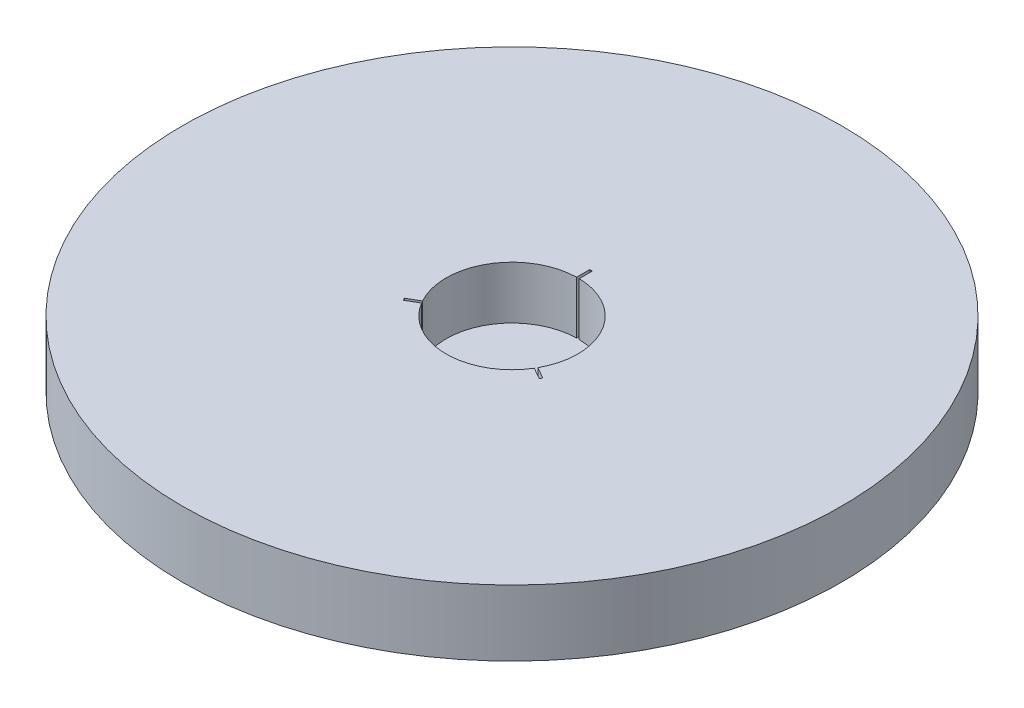
SolidWorks part; units mm, degrees
ref_plane "前基準面" through (0, 0, 0) normal (0, 0, 1) x (1, 0, 0)
ref_plane "上基準面" through (0, 0, 0) normal (0, 1, 0) x (1, 0, 0)
ref_plane "右基準面" through (0, 0, 0) normal (1, 0, 0) x (0, 0, -1)
sketch "草圖2" plane through (0, 0, 0) normal (0, 1, 0) x (1, 0, 0)
  line L0 (26.2264, -14.5645) -> (25.7264, -15.4305)
  line L1 (-0.5, 29.995) -> (0.5, 29.995)
  line L2 (-0.5, 29.995) -> (-0.5, 24.995)
  line L3 (0.5, 29.995) -> (0.5, 24.995)
  line L4 (-0.5, 29.995) -> (0.5, 24.995) construction
  line L5 (-0.5, 24.995) -> (0.5, 29.995) construction
  line L6 (26.2264, -14.5645) -> (21.8963, -12.0645)
  line L7 (25.7264, -15.4305) -> (21.3963, -12.9305)
  line L8 (26.2264, -14.5645) -> (21.3963, -12.9305) construction
  line L9 (21.8963, -12.0645) -> (25.7264, -15.4305) construction
  line L10 (-25.7264, -15.4305) -> (-26.2264, -14.5645)
  line L11 (-25.7264, -15.4305) -> (-21.3963, -12.9305)
  line L12 (-26.2264, -14.5645) -> (-21.8963, -12.0645)
  line L13 (-25.7264, -15.4305) -> (-21.8963, -12.0645) construction
  line L14 (-21.3963, -12.9305) -> (-26.2264, -14.5645) construction
  circle A0 centre (0, 0) radius 125
  arc A6 (-0.5, 24.995) -> (-21.8963, -12.0645) centre (0, 0) ccw
  arc A7 (-21.3963, -12.9305) -> (21.3963, -12.9305) centre (0, 0) ccw
  arc A8 (21.8963, -12.0645) -> (0.5, 24.995) centre (0, 0) ccw
  point P5 (0, 27.495)
  point P14 (0, 0)
  dimension "D1" = 250
  dimension "D2" = 50
  dimension "D3" = 1
  dimension "D4" = 5
  dimension "D5" = 1
  dimension "D6" = 5
  dimension "D7" = 1
  dimension "D8" = 5
extrude "填料-伸長1" add sketch "草圖2" along normal blind 25
sketch "草圖3" plane through (0, 0, 0) normal (0, -1, 0) x (1, 0, 0)
  circle A1 centre (0, 0) radius 125
  circle A2 centre (0, 0) radius 125
  dimension "D1" = 0
extrude "填料-伸長2" add sketch "草圖3" against normal blind 5
